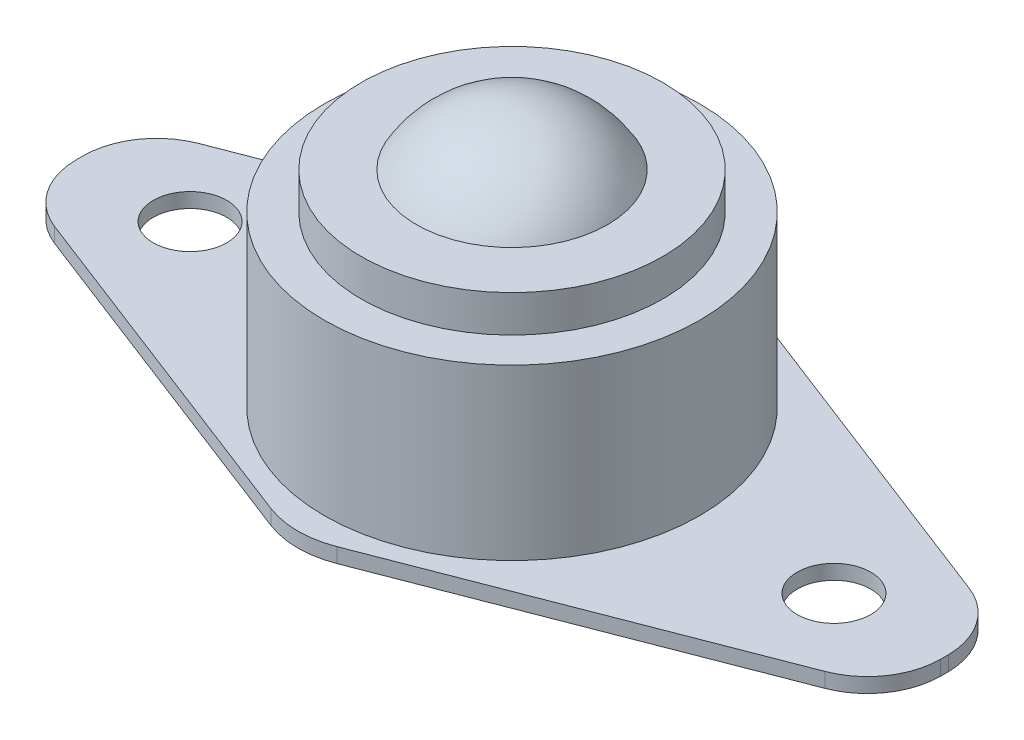
SolidWorks part; units mm, degrees
ref_plane "정면" through (0, 0, 0) normal (0, 0, 1) x (1, 0, 0)
ref_plane "윗면" through (0, 0, 0) normal (0, 1, 0) x (1, 0, 0)
ref_plane "우측면" through (0, 0, 0) normal (1, 0, 0) x (0, 0, -1)
sketch "Sketch1" plane through (0, 0, 0) normal (0, 0, 1) x (1, 0, 0)
  line L0 (-5.1962, 12) -> (-8.1962, 12)
  line L1 (0, 0) -> (-23.5, 0)
  line L2 (0, 0) -> (0, 15) construction
  line L3 (0, 15) -> (-23.5, 15) construction
  line L4 (-23.5, 0) -> (-23.5, 15) construction
  line L5 (-8.1962, 12) -> (-8.1962, 10)
  line L6 (-8.1962, 10) -> (-10.1962, 10)
  line L7 (-10.1962, 10) -> (-10.1962, 0.8)
  line L8 (-10.1962, 0.8) -> (-23.5, 0.8)
  line L9 (-23.5, 0.8) -> (-23.5, 0)
  line L10 (0, 0) -> (0, 15)
  arc A0 (0, 15) -> (-5.1962, 12) centre (0, 9) ccw
  dimension "D2" = 12
  dimension "D1" = 15
  dimension "D3" = 12
  dimension "D4" = 47
  dimension "D5" = 0.8
  dimension "D6" = 3
  dimension "D7" = 2
  dimension "D8" = 10
revolve "Revolve1" add sketch "Sketch1" angle 360 about L10
sketch "Sketch2" plane through (0, 0, 0) normal (0, 1, 0) x (1, 0, 0)
  line L0 (-17.5, 0) -> (17.5, 0) construction
  circle A0 centre (-17.5, 0) radius 2
  circle A1 centre (17.5, 0) radius 2
  point P6 (17.5, 0.448)
  dimension "D2" = 4
  dimension "D3" = 4
  dimension "D1" = 35
extrude "Cut-Extrude3" cut sketch "Sketch2" against normal through all and the other way through all
sketch "Sketch3" plane through (0, 0, 0) normal (0, 1, 0) x (1, 0, 0)
  line L0 (-23.3077, 3) -> (0, 12)
  line L1 (0, 12) -> (23.3077, 3)
  line L6 (-23.5, 0) -> (23.5, 0) construction
  line L7 (0, -12) -> (23.3077, -3)
  line L8 (-23.3077, -3) -> (0, -12)
  circle A0 centre (0, 0) radius 23.5 construction
  arc A1 (23.3077, 3) -> (-23.3077, 3) centre (0, 0) ccw
  arc A2 (-23.3077, -3) -> (23.3077, -3) centre (0, 0) ccw
  point P9 (-23.2342, 3.5243)
  point P10 (-23.3311, 2.8126)
  point P12 (0, 12)
  dimension "D1" = 3
  dimension "D2" = 12
extrude "Cut-Extrude4" cut sketch "Sketch3" along normal through all contours L0 L1 A1 | L8 L7 A2
fillet "Fillet1" radius 4 4 edges at (23.3077, 0.4, 3) (23.3077, 0.4, -3) (-23.3077, 0.4, 3) (-23.3077, 0.4, -3)
fillet "Fillet2" radius 5 2 edges at (0, 0.4, 12) (0, 0.4, -12)
